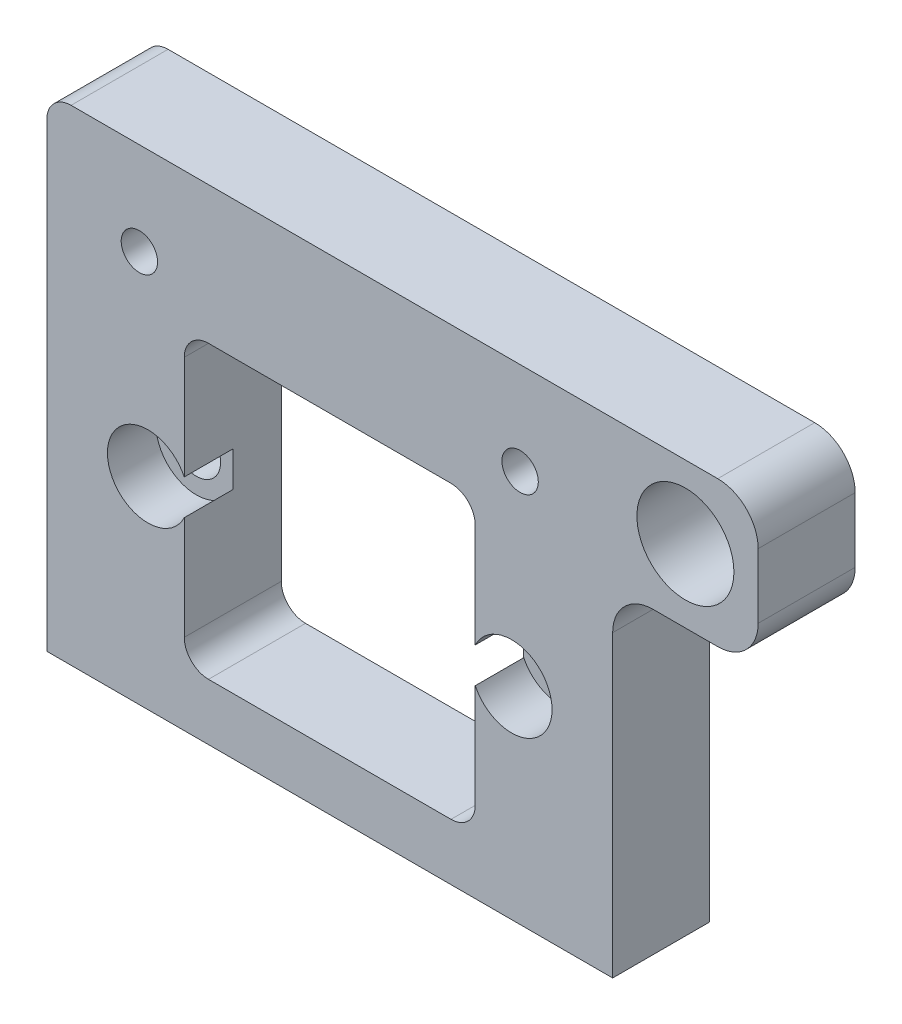
SolidWorks part; units mm, degrees
ref_plane "Plan de face" through (0, 0, 0) normal (0, 0, 1) x (1, 0, 0)
ref_plane "Plan de dessus" through (0, 0, 0) normal (0, 1, 0) x (1, 0, 0)
ref_plane "Plan de droite" through (0, 0, 0) normal (1, 0, 0) x (0, 0, -1)
sketch "Esquisse1" plane through (0, 0, 0) normal (0, 0, 1) x (1, 0, 0)
  line L1 (0, 0) -> (70, 0)
  line L2 (0, 0) -> (0, 57)
  line L3 (3, 60) -> (70, 60)
  line L4 (70, 0) -> (70, 37)
  line L5 (20, 7) -> (50, 7)
  line L6 (17, 10) -> (17, 40)
  line L7 (20, 43) -> (50, 43)
  line L8 (53, 10) -> (53, 40)
  line L9 (75, 42) -> (83, 42)
  line L11 (70, 60) -> (83, 60)
  line L12 (88, 47) -> (88, 55)
  circle A0 centre (79, 51) radius 6
  arc A1 (3, 60) -> (0, 57) centre (3, 57) ccw
  arc A2 (17, 40) -> (20, 43) centre (20, 40) cw
  arc A3 (50, 43) -> (53, 40) centre (50, 40) cw
  arc A4 (53, 10) -> (50, 7) centre (50, 10) cw
  arc A5 (20, 7) -> (17, 10) centre (20, 10) cw
  arc A6 (70, 37) -> (75, 42) centre (75, 37) cw
  arc A7 (83, 42) -> (88, 47) centre (83, 47) ccw
  arc A8 (88, 55) -> (83, 60) centre (83, 55) ccw
  point P13 (0, 60)
  point P16 (17, 43)
  point P19 (53, 43)
  point P22 (53, 7)
  point P30 (70, 42)
  point P33 (88, 42)
  point P36 (88, 60)
  dimension "D7" = 12
  dimension "D10" = 9
  dimension "D11" = 9
  dimension "D12" = 5
  dimension "D1" = 60
  dimension "D2" = 70
  dimension "D3" = 36
  dimension "D4" = 36
  dimension "D5" = 7
  dimension "D6" = 17
  dimension "D8" = 18
  dimension "D9" = 18
extrude "Boss.-Extru.1" add sketch "Esquisse1" along normal blind 12
sketch "Esquisse2" plane through (0, 0, 12) normal (0, 0, 1) x (1, 0, 0)
  line L0 (35, 0) -> (35, 61.4005) construction
  line L1 (0, 0) -> (70, 0) construction
  line L2 (17, 25) -> (-3.726, 25) construction
  line L3 (17, 40) -> (17, 10) construction
  circle A0 centre (12.5, 25) radius 3
  circle A1 centre (57.5, 25) radius 3
  dimension "D1" = 6
  dimension "D2" = 22.5
extrude "Enlèv. mat.-Extru.1" cut sketch "Esquisse2" against normal blind 12
sketch "Esquisse3" plane through (0, 0, 12) normal (0, 0, 1) x (1, 0, 0)
  circle A0 centre (12.5, 25) radius 5
  circle A1 centre (57.5, 25) radius 5
  dimension "D1" = 10
  dimension "D2" = 10
extrude "Enlèv. mat.-Extru.2" cut sketch "Esquisse3" against normal blind 6
sketch "Esquisse4" plane through (0, 0, 12) normal (0, 0, 1) x (1, 0, 0)
  line L0 (17.8787, 42.1213) -> (52.1213, 7.8787) construction
  line L1 (52.1213, 42.1213) -> (17.8787, 7.8787) construction
  line L3 (11.45, 48.55) -> (58.55, 48.55) construction
  line L4 (11.45, 48.55) -> (11.45, 1.45) construction
  line L5 (11.45, 1.45) -> (58.55, 1.45) construction
  line L6 (58.55, 48.55) -> (58.55, 1.45) construction
  line L7 (11.45, 48.55) -> (58.55, 1.45) construction
  line L8 (11.45, 1.45) -> (58.55, 48.55) construction
  circle A0 centre (11.45, 48.55) radius 2.25
  circle A1 centre (58.55, 48.55) radius 2.25
  point P2 (35, 25)
  dimension "D3" = 4.5
  dimension "D4" = 4.5
  dimension "D1" = 47.1
  dimension "D2" = 47.1
extrude "Enlèv. mat.-Extru.3" cut sketch "Esquisse4" against normal up to next
